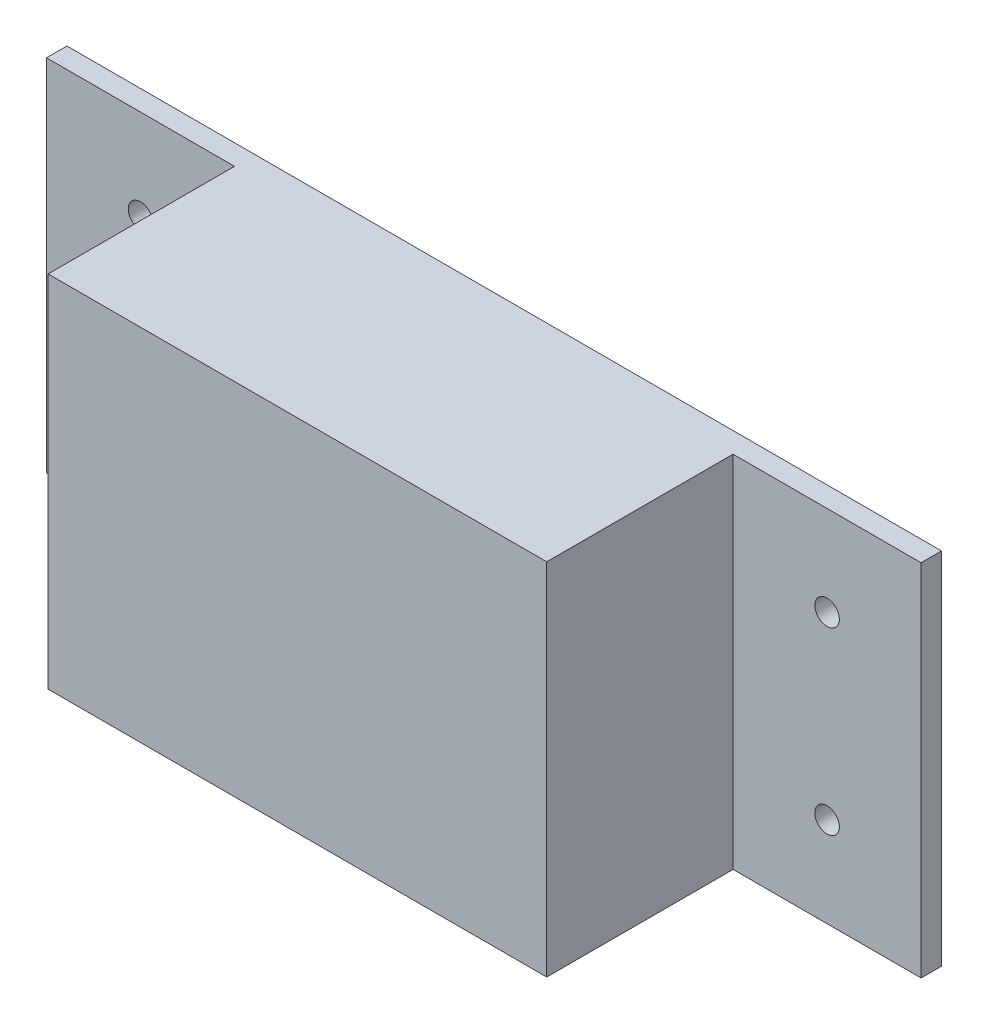
SolidWorks part; units mm, degrees
ref_plane "Front Plane" through (0, 0, 0) normal (0, 0, 1) x (1, 0, 0)
ref_plane "Top Plane" through (0, 0, 0) normal (0, 1, 0) x (1, 0, 0)
ref_plane "Right Plane" through (0, 0, 0) normal (1, 0, 0) x (0, 0, -1)
sketch "Sketch1" plane through (0, 0, 0) normal (0, 0, 1) x (1, 0, 0)
  line L0 (-30.5, 22) -> (-30.5, -22)
  line L1 (-27.5, 19) -> (27.5, 19)
  line L2 (-27.5, 19) -> (-27.5, -19)
  line L3 (-27.5, -19) -> (27.5, -19)
  line L4 (27.5, 19) -> (27.5, -19)
  line L5 (-27.5, 19) -> (27.5, -19) construction
  line L6 (-27.5, -19) -> (27.5, 19) construction
  line L7 (-30.5, -22) -> (30.5, -22)
  line L8 (30.5, 22) -> (30.5, -22)
  line L9 (-30.5, 22) -> (30.5, 22)
  point P0 (0, 0)
  dimension "D1" = 55
  dimension "D2" = 3
  dimension "D3" = 38
extrude "Boss-Extrude1" add sketch "Sketch1" along normal blind 23 contours L4 L1 L2 L3 | L0 L7 L8 L9
sketch "Sketch2" plane through (0, 0, 23) normal (0, 0, 1) x (1, 0, 0)
  line L1 (-30.5, 22) -> (30.5, 22)
  line L2 (-30.5, 22) -> (-30.5, -22)
  line L3 (-30.5, -22) -> (30.5, -22)
  line L4 (30.5, 22) -> (30.5, -22)
extrude "Boss-Extrude2" add sketch "Sketch2" along normal blind 2.3
sketch "Sketch3" plane through (-30.5, 0, 0) normal (-1, 0, 0) x (0, 0, 1)
  line L0 (25.3, -22) -> (0, -22) construction
  line L1 (0, 22) -> (2.5, 22)
  line L2 (0, 22) -> (0, -22)
  line L3 (0, -22) -> (2.5, -22)
  line L4 (2.5, 22) -> (2.5, -22)
  dimension "D1" = 2.5
extrude "Boss-Extrude3" add sketch "Sketch3" along normal blind 23 contours L2 L1 L4 L3
sketch "Sketch5" plane through (30.5, 0, 0) normal (1, 0, 0) x (0, 0, -1)
  line L0 (-25.3, -22) -> (0, -22) construction
  line L1 (0, 22) -> (-2.5, 22)
  line L2 (0, 22) -> (0, -22)
  line L3 (0, -22) -> (-2.5, -22)
  line L4 (-2.5, 22) -> (-2.5, -22)
  dimension "D1" = 2.5
extrude "Boss-Extrude4" add sketch "Sketch5" along normal blind 23
sketch "Sketch6" plane through (0, 0, 2.5) normal (0, 0, 1) x (1, 0, 0)
  line L0 (42, 0) -> (42, 22) construction
  line L1 (53.5, 22) -> (30.5, 22) construction
  line L3 (30.5, -22) -> (30.5, 22) construction
  line L4 (53.5, 0) -> (30.5, 0) construction
  line L5 (53.5, 22) -> (53.5, -22) construction
  line L6 (53.5, 9.26) -> (30.5, 9.26) construction
  line L7 (30.5, 22) -> (30.5, -22) construction
  line L8 (0, 0) -> (0, -5.2023)
  circle A0 centre (42, 11) radius 1.5
  circle A1 centre (42, -11) radius 1.5
  circle A2 centre (-42, -11) radius 1.5
  circle A3 centre (-42, 11) radius 1.5
  dimension "D2" = 22
  dimension "D3" = 9.26
extrude "Cut-Extrude1" cut sketch "Sketch6" against normal blind 23 contours A3 | A2 | A0 | A1
